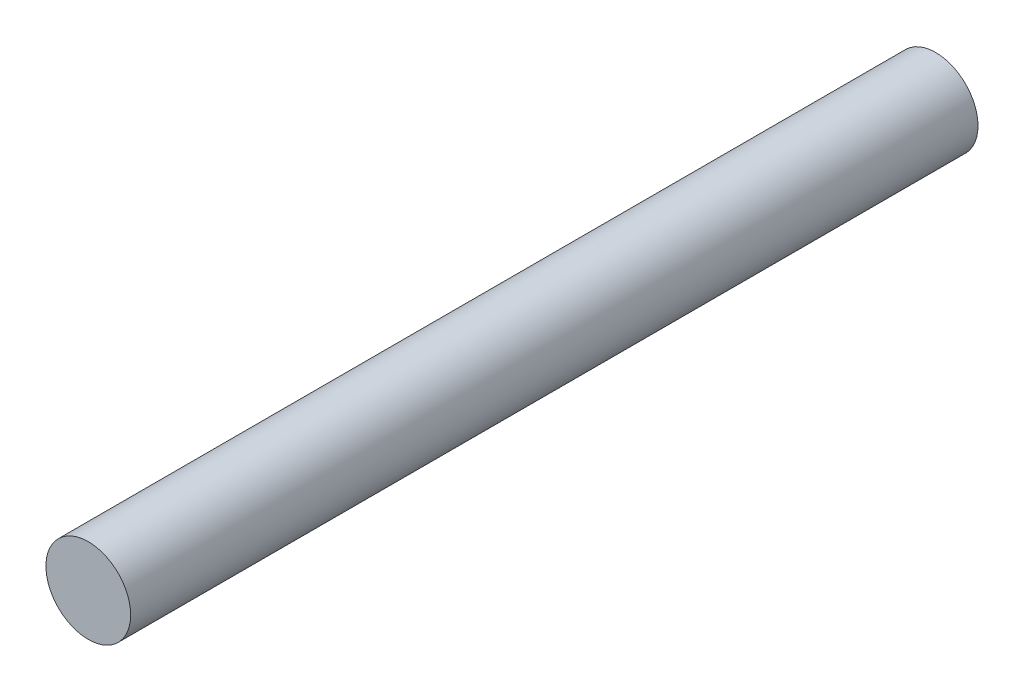
SolidWorks part; units mm, degrees
ref_plane "Alzado" through (0, 0, 0) normal (0, 0, 1) x (1, 0, 0)
ref_plane "Planta" through (0, 0, 0) normal (0, 1, 0) x (1, 0, 0)
ref_plane "Vista lateral" through (0, 0, 0) normal (1, 0, 0) x (0, 0, -1)
sketch "Croquis1" plane through (0, 0, 0) normal (0, 0, 1) x (1, 0, 0)
  circle A0 centre (0, 0) radius 1
  dimension "D1" = 2
extrude "Saliente-Extruir1" add sketch "Croquis1" along normal blind 20
